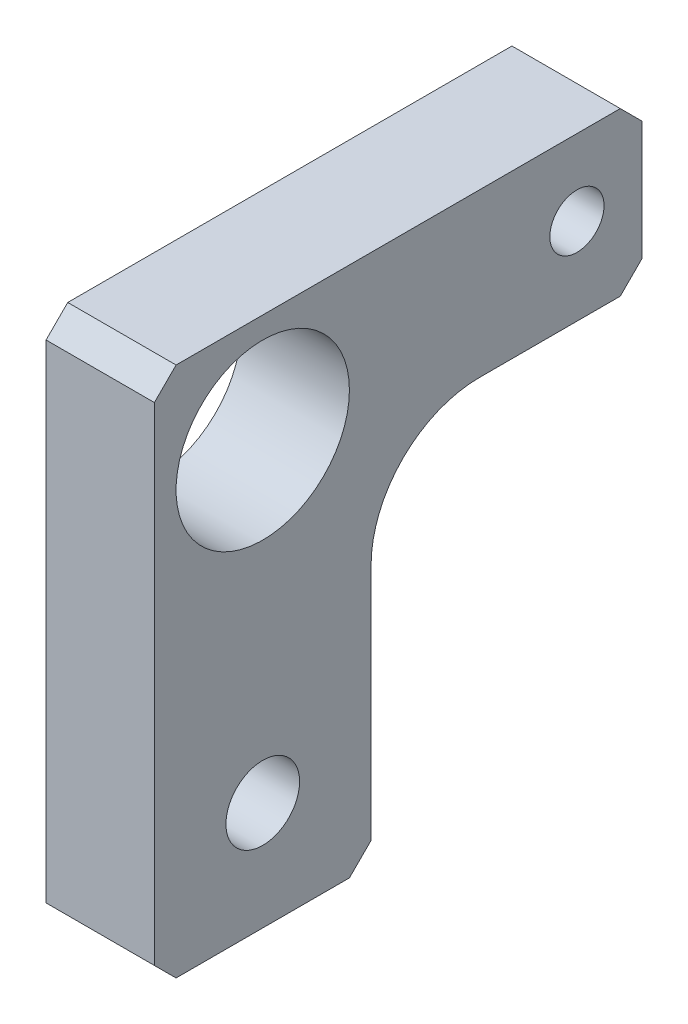
SolidWorks part; units mm, degrees
ref_plane "Front" through (0, 0, 0) normal (0, 0, 1) x (1, 0, 0)
ref_plane "Top" through (0, 0, 0) normal (0, 1, 0) x (1, 0, 0)
ref_plane "Right" through (0, 0, 0) normal (1, 0, 0) x (0, 0, -1)
sketch "Sketch1" plane through (0, 0, 0) normal (1, 0, 0) x (0, 0, -1)
  line L1 (0, 0) -> (45, 0)
  line L2 (0, 0) -> (0, -49)
  line L3 (0, -49) -> (45, -49)
  line L4 (45, 0) -> (45, -49)
  dimension "D1" = 49
  dimension "D2" = 45
extrude "Boss-Extrude1" add sketch "Sketch1" along normal mid plane 10
sketch "Sketch2" plane through (5, 0, 0) normal (1, 0, 0) x (0, 0, -1)
  line L0 (0, 0) -> (0, -49) construction
  line L1 (45, -49) -> (20, -49)
  line L2 (45, -49) -> (45, -15)
  line L3 (45, -15) -> (20, -15)
  line L4 (20, -49) -> (20, -15)
  line L5 (45, 0) -> (0, 0) construction
  dimension "D1" = 20
  dimension "D2" = 15
extrude "Cut-Extrude1" cut sketch "Sketch2" against normal through all
sketch "Sketch3" plane through (5, 0, 0) normal (1, 0, 0) x (0, 0, -1)
  line L0 (0, 0) -> (0, -49) construction
  line L1 (45, 0) -> (0, 0) construction
  circle A0 centre (10, -10) radius 8
  dimension "D1" = 16
  dimension "D2" = 10
  dimension "D3" = 10
extrude "Cut-Extrude2" cut sketch "Sketch3" against normal through all
hole_wizard "M8x1.25 Tapped Hole1" positions "Sketch5" profile "Sketch4" tap size "M8x1.25" standard "JIS" end condition through all
sketch "Sketch5" plane through (5, 0, 0) normal (1, 0, 0) x (0, 0, -1)
  line L0 (0, 0) -> (0, -49) construction
  line L1 (45, 0) -> (0, 0) construction
  point P0 (10, -39)
  dimension "D1" = 10
  dimension "D2" = 39
sketch "Sketch4" plane through (5, -39, -10) normal (0, 1, 0) x (0, 0, -1)
  line L0 (0, 0) -> (0, 10)
  line L1 (0, 10) -> (3.4, 10)
  line L2 (3.4, 10) -> (3.4, 0)
  line L5 (3.4, 0) -> (0, 0)
  line L11 (0, -6.35) -> (0, 107.95) construction
  dimension "Thru Tap Drill Dia." = 6.8
  dimension "Thru Tap Drill Depth" = 10
cosmetic thread "Hole Thread1" parameters "D2"=8
hole_wizard "M6x1.0 Tapped Hole1" positions "Sketch7" profile "Sketch6" tap size "M6x1.0" standard "JIS" end condition through all
sketch "Sketch7" plane through (5, 0, 0) normal (1, 0, 0) x (0, 0, -1)
  line L0 (0, 0) -> (0, -49) construction
  line L1 (45, 0) -> (0, 0) construction
  point P0 (39, -7)
  dimension "D1" = 39
  dimension "D2" = 7
sketch "Sketch6" plane through (5, -7, -39) normal (0, 1, 0) x (0, 0, -1)
  line L0 (0, 0) -> (0, 10)
  line L1 (0, 10) -> (2.5, 10)
  line L2 (2.5, 10) -> (2.5, 0)
  line L5 (2.5, 0) -> (0, 0)
  line L11 (0, -6.35) -> (0, 107.95) construction
  dimension "Thru Tap Drill Dia." = 5
  dimension "Thru Tap Drill Depth" = 10
cosmetic thread "Hole Thread2" parameters "D2"=6
fillet "Fillet1" radius 10 1 edges at (0, -15, -20)
chamfer "Chamfer1" distance 2 angle 45 5 edges at (0, -49, 0) (0, -49, -20) (0, -15, -45) (0, 0, -45) (0, 0, 0)
